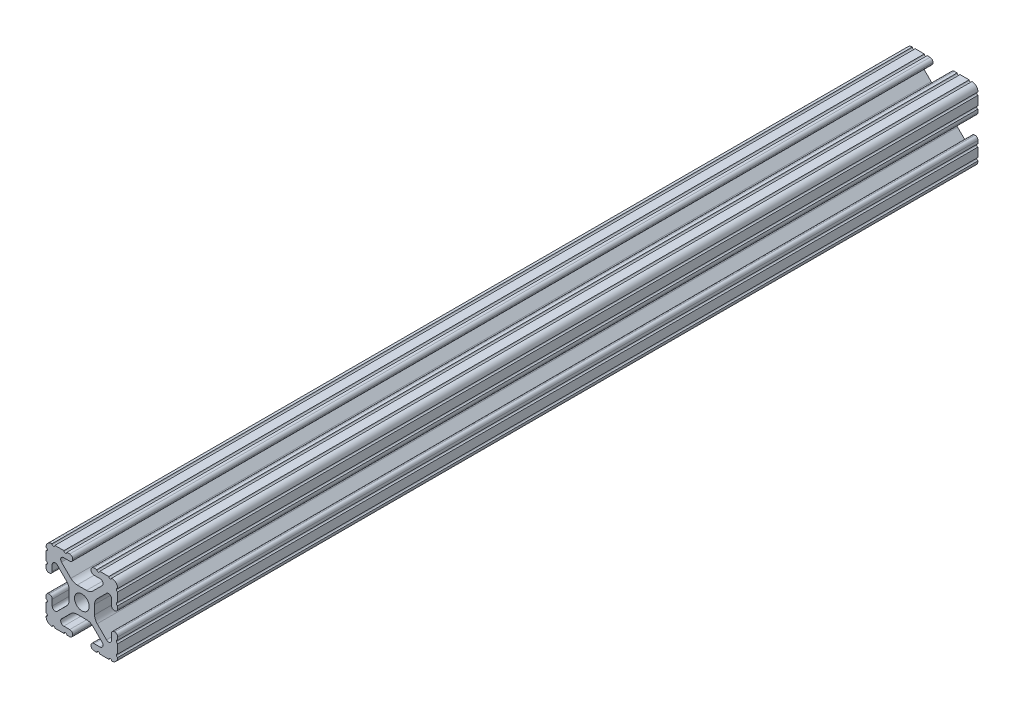
SolidWorks part; units mm, degrees
ref_plane "Front Plane" through (0, 0, 0) normal (0, 0, 1) x (1, 0, 0)
ref_plane "Top Plane" through (0, 0, 0) normal (0, 1, 0) x (1, 0, 0)
ref_plane "Right Plane" through (0, 0, 0) normal (1, 0, 0) x (0, 0, -1)
sketch "Sketch1" plane through (0, 0, 0) normal (0, 0, 1) x (1, 0, 0)
  line L88 (-7.1797, -8.6452) -> (-3.9523, -5.4237)
  line L89 (-1.7093, -4.4958) -> (1.7093, -4.4958)
  line L90 (3.9523, -5.4237) -> (7.1797, -8.6452)
  line L91 (6.4164, -10.4902) -> (4.2875, -10.4902)
  line L92 (3.2385, -11.5392) -> (3.2385, -11.651)
  line L93 (4.2875, -12.7) -> (5.3171, -12.7)
  line L94 (6.3331, -12.7) -> (9.5504, -12.7)
  line L95 (12.7, -9.5504) -> (12.7, -6.3331)
  line L96 (12.7, -5.3171) -> (12.7, -4.2875)
  line L97 (11.651, -3.2385) -> (11.5392, -3.2385)
  line L98 (10.4902, -4.2875) -> (10.4902, -6.4021)
  line L99 (8.7371, -7.1294) -> (5.441, -3.8408)
  line L100 (4.5085, -1.5932) -> (4.5085, 1.5932)
  line L101 (5.441, 3.8408) -> (8.7371, 7.1294)
  line L102 (10.4902, 6.4021) -> (10.4902, 4.2875)
  line L103 (11.5392, 3.2385) -> (11.651, 3.2385)
  line L104 (12.7, 4.2875) -> (12.7, 5.3171)
  line L105 (12.7, 6.3331) -> (12.7, 9.5504)
  line L106 (9.5504, 12.7) -> (6.3331, 12.7)
  line L107 (5.3171, 12.7) -> (4.2875, 12.7)
  line L108 (3.2385, 11.651) -> (3.2385, 11.5392)
  line L109 (4.2875, 10.4902) -> (6.4768, 10.4902)
  line L110 (7.207, 8.7244) -> (3.8983, 5.4232)
  line L111 (1.6558, 4.4958) -> (-1.6558, 4.4958)
  line L112 (-3.8983, 5.4232) -> (-7.207, 8.7244)
  line L113 (-6.4768, 10.4902) -> (-4.2875, 10.4902)
  line L114 (-3.2385, 11.5392) -> (-3.2385, 11.651)
  line L115 (-4.2875, 12.7) -> (-5.3171, 12.7)
  line L116 (-6.3331, 12.7) -> (-9.5504, 12.7)
  line L117 (-12.7, 9.5504) -> (-12.7, 6.3331)
  line L118 (-12.7, 5.3171) -> (-12.7, 4.2875)
  line L119 (-11.651, 3.2385) -> (-11.5392, 3.2385)
  line L120 (-10.4902, 4.2875) -> (-10.4902, 6.4021)
  line L121 (-8.7371, 7.1294) -> (-5.441, 3.8408)
  line L122 (-4.5085, 1.5932) -> (-4.5085, -1.5932)
  line L123 (-5.441, -3.8408) -> (-8.7371, -7.1294)
  line L124 (-10.4902, -6.4021) -> (-10.4902, -4.2875)
  line L125 (-11.5392, -3.2385) -> (-11.651, -3.2385)
  line L126 (-12.7, -4.2875) -> (-12.7, -5.3171)
  line L127 (-12.7, -6.3331) -> (-12.7, -9.5504)
  line L128 (-9.5504, -12.7) -> (-6.3331, -12.7)
  line L129 (-5.3171, -12.7) -> (-4.2875, -12.7)
  line L130 (-3.2385, -11.651) -> (-3.2385, -11.5392)
  line L131 (-4.2875, -10.4902) -> (-6.4164, -10.4902)
  circle A1 centre (0, 0) radius 2.6035
  arc A104 (-7.1797, -8.6452) -> (-6.4164, -10.4902) centre (-6.4164, -9.4098) ccw
  arc A105 (-1.7093, -4.4958) -> (-3.9523, -5.4237) centre (-1.7093, -7.6708) ccw
  arc A106 (3.9523, -5.4237) -> (1.7093, -4.4958) centre (1.7093, -7.6708) ccw
  arc A107 (6.4164, -10.4902) -> (7.1797, -8.6452) centre (6.4164, -9.4098) ccw
  arc A108 (4.2875, -10.4902) -> (3.2385, -11.5392) centre (4.2875, -11.5392) ccw
  arc A109 (3.2385, -11.651) -> (4.2875, -12.7) centre (4.2875, -11.651) ccw
  arc A110 (6.3331, -12.7) -> (5.3171, -12.7) centre (5.8251, -12.7) ccw
  arc A111 (10.5664, -12.6998) -> (9.5504, -12.7) centre (10.0584, -12.7) ccw
  arc A112 (10.5664, -12.6998) -> (12.6998, -10.5664) centre (10.5918, -10.5918) ccw
  arc A113 (12.7, -9.5504) -> (12.6998, -10.5664) centre (12.7, -10.0584) ccw
  arc A114 (12.7, -5.3171) -> (12.7, -6.3331) centre (12.7, -5.8251) ccw
  arc A115 (12.7, -4.2875) -> (11.651, -3.2385) centre (11.651, -4.2875) ccw
  arc A116 (11.5392, -3.2385) -> (10.4902, -4.2875) centre (11.5392, -4.2875) ccw
  arc A117 (8.7371, -7.1294) -> (10.4902, -6.4021) centre (9.4628, -6.4021) ccw
  arc A118 (4.5085, -1.5932) -> (5.441, -3.8408) centre (7.6835, -1.5932) ccw
  arc A119 (5.441, 3.8408) -> (4.5085, 1.5932) centre (7.6835, 1.5932) ccw
  arc A120 (10.4902, 6.4021) -> (8.7371, 7.1294) centre (9.4628, 6.4021) ccw
  arc A121 (10.4902, 4.2875) -> (11.5392, 3.2385) centre (11.5392, 4.2875) ccw
  arc A122 (11.651, 3.2385) -> (12.7, 4.2875) centre (11.651, 4.2875) ccw
  arc A123 (12.7, 6.3331) -> (12.7, 5.3171) centre (12.7, 5.8251) ccw
  arc A124 (12.6998, 10.5664) -> (12.7, 9.5504) centre (12.7, 10.0584) ccw
  arc A125 (12.6998, 10.5664) -> (10.5664, 12.6998) centre (10.5918, 10.5918) ccw
  arc A126 (9.5504, 12.7) -> (10.5664, 12.6998) centre (10.0584, 12.7) ccw
  arc A127 (5.3171, 12.7) -> (6.3331, 12.7) centre (5.8251, 12.7) ccw
  arc A128 (4.2875, 12.7) -> (3.2385, 11.651) centre (4.2875, 11.651) ccw
  arc A129 (3.2385, 11.5392) -> (4.2875, 10.4902) centre (4.2875, 11.5392) ccw
  arc A130 (7.207, 8.7244) -> (6.4768, 10.4902) centre (6.4768, 9.4563) ccw
  arc A131 (1.6558, 4.4958) -> (3.8983, 5.4232) centre (1.6558, 7.6708) ccw
  arc A132 (-3.8983, 5.4232) -> (-1.6558, 4.4958) centre (-1.6558, 7.6708) ccw
  arc A133 (-6.4768, 10.4902) -> (-7.207, 8.7244) centre (-6.4768, 9.4563) ccw
  arc A134 (-4.2875, 10.4902) -> (-3.2385, 11.5392) centre (-4.2875, 11.5392) ccw
  arc A135 (-3.2385, 11.651) -> (-4.2875, 12.7) centre (-4.2875, 11.651) ccw
  arc A136 (-6.3331, 12.7) -> (-5.3171, 12.7) centre (-5.8251, 12.7) ccw
  arc A137 (-10.5664, 12.6998) -> (-9.5504, 12.7) centre (-10.0584, 12.7) ccw
  arc A138 (-10.5664, 12.6998) -> (-12.6998, 10.5664) centre (-10.5918, 10.5918) ccw
  arc A139 (-12.7, 9.5504) -> (-12.6998, 10.5664) centre (-12.7, 10.0584) ccw
  arc A140 (-12.7, 5.3171) -> (-12.7, 6.3331) centre (-12.7, 5.8251) ccw
  arc A141 (-12.7, 4.2875) -> (-11.651, 3.2385) centre (-11.651, 4.2875) ccw
  arc A142 (-11.5392, 3.2385) -> (-10.4902, 4.2875) centre (-11.5392, 4.2875) ccw
  arc A143 (-8.7371, 7.1294) -> (-10.4902, 6.4021) centre (-9.4628, 6.4021) ccw
  arc A144 (-4.5085, 1.5932) -> (-5.441, 3.8408) centre (-7.6835, 1.5932) ccw
  arc A145 (-5.441, -3.8408) -> (-4.5085, -1.5932) centre (-7.6835, -1.5932) ccw
  arc A146 (-10.4902, -6.4021) -> (-8.7371, -7.1294) centre (-9.4628, -6.4021) ccw
  arc A147 (-10.4902, -4.2875) -> (-11.5392, -3.2385) centre (-11.5392, -4.2875) ccw
  arc A148 (-11.651, -3.2385) -> (-12.7, -4.2875) centre (-11.651, -4.2875) ccw
  arc A149 (-12.7, -6.3331) -> (-12.7, -5.3171) centre (-12.7, -5.8251) ccw
  arc A150 (-12.6998, -10.5664) -> (-12.7, -9.5504) centre (-12.7, -10.0584) ccw
  arc A151 (-12.6998, -10.5664) -> (-10.5664, -12.6998) centre (-10.5918, -10.5918) ccw
  arc A152 (-9.5504, -12.7) -> (-10.5664, -12.6998) centre (-10.0584, -12.7) ccw
  arc A153 (-5.3171, -12.7) -> (-6.3331, -12.7) centre (-5.8251, -12.7) ccw
  arc A154 (-4.2875, -12.7) -> (-3.2385, -11.651) centre (-4.2875, -11.651) ccw
  arc A155 (-3.2385, -11.5392) -> (-4.2875, -10.4902) centre (-4.2875, -11.5392) ccw
extrude "Boss-Extrude1" add sketch "Sketch1" along normal mid plane 609.6
sketch "Sketch2" plane through (0, 0, -304.8) normal (0, 0, -1) x (-1, 0, 0)
  circle A0 centre (0, 0) radius 27.8815
extrude "Cut-Extrude1" cut sketch "Sketch2" against normal blind 304.8
